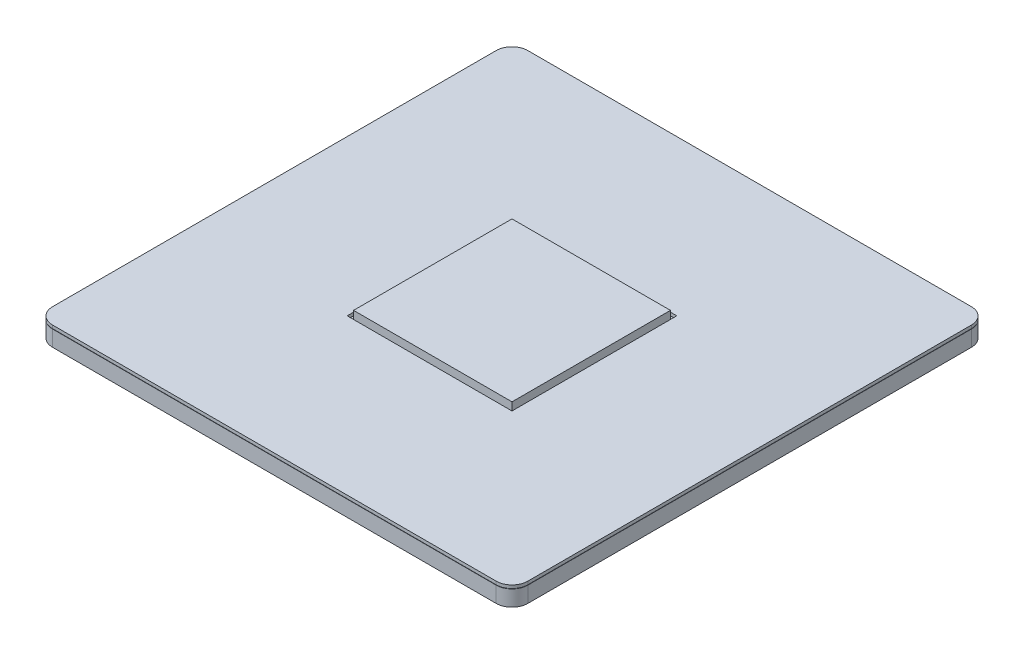
SolidWorks part; units mm, degrees
ref_plane "前视基准面" through (0, 0, 0) normal (0, 0, 1) x (1, 0, 0)
ref_plane "上视基准面" through (0, 0, 0) normal (0, 1, 0) x (1, 0, 0)
ref_plane "右视基准面" through (0, 0, 0) normal (1, 0, 0) x (0, 0, -1)
sketch "草图1" plane through (0, 0, 0) normal (0, 1, 0) x (1, 0, 0)
  line L1 (-7.5, -7.5) -> (7.5, -7.5)
  line L2 (-7.5, -7.5) -> (-7.5, 7.5)
  line L3 (-7.5, 7.5) -> (7.5, 7.5)
  line L4 (7.5, -7.5) -> (7.5, 7.5)
  line L5 (-7.5, -7.5) -> (7.5, 7.5) construction
  line L6 (-7.5, 7.5) -> (7.5, -7.5) construction
  point P0 (0, 0)
  dimension "D1" = 15
  dimension "D2" = 45
extrude "凸台-拉伸1" add sketch "草图1" along normal blind 0.5
fillet "圆角1" radius 0.5 4 edges at (-7.5, 0.25, 7.5) (-7.5, 0.25, -7.5) (7.5, 0.25, -7.5) (7.5, 0.25, 7.5)
ref_plane "基准面1" through (0, 0.51, 0) normal (0, 1, 0) x (1, 0, 0)
sketch "草图2" plane through (0, 0.51, 0) normal (0, 1, 0) x (1, 0, 0)
  line L1 (-2.6, -2.6) -> (2.6, -2.6)
  line L2 (-2.6, -2.6) -> (-2.6, 2.6)
  line L3 (-2.6, 2.6) -> (2.6, 2.6)
  line L4 (-7.5, 7) -> (-7.5, -7)
  line L5 (-7, -7.5) -> (7, -7.5)
  line L6 (7.5, -7) -> (7.5, 7)
  line L7 (7, 7.5) -> (-7, 7.5)
  line L8 (-7.5, 7) -> (-7.5, -7)
  line L9 (-7, -7.5) -> (7, -7.5)
  line L10 (7.5, -7) -> (7.5, 7)
  line L11 (7, 7.5) -> (-7, 7.5)
  line L12 (2.6, -2.6) -> (2.6, 2.6)
  line L13 (-2.6, -2.6) -> (2.6, 2.6) construction
  line L14 (-2.6, 2.6) -> (2.6, -2.6) construction
  arc A4 (-7.5, -7) -> (-7, -7.5) centre (-7, -7) ccw
  arc A5 (7, -7.5) -> (7.5, -7) centre (7, -7) ccw
  arc A6 (7.5, 7) -> (7, 7.5) centre (7, 7) ccw
  arc A7 (-7, 7.5) -> (-7.5, 7) centre (-7, 7) ccw
  arc A8 (-7.5, -7) -> (-7, -7.5) centre (-7, -7) ccw
  arc A9 (7, -7.5) -> (7.5, -7) centre (7, -7) ccw
  arc A10 (7.5, 7) -> (7, 7.5) centre (7, 7) ccw
  arc A11 (-7, 7.5) -> (-7.5, 7) centre (-7, 7) ccw
  point P2 (0, 0)
  dimension "D2" = 5.2
  dimension "D3" = 45
  dimension "D1" = 0
extrude "凸台-拉伸2" add sketch "草图2" along normal blind 0.1
sketch "草图3" plane through (0, 0.51, 0) normal (0, 1, 0) x (1, 0, 0)
  line L1 (-2.5, -2.5) -> (2.5, -2.5)
  line L2 (-2.5, -2.5) -> (-2.5, 2.5)
  line L3 (-2.5, 2.5) -> (2.5, 2.5)
  line L4 (2.5, -2.5) -> (2.5, 2.5)
  line L5 (-2.5, -2.5) -> (2.5, 2.5) construction
  line L6 (-2.5, 2.5) -> (2.5, -2.5) construction
  point P0 (0, 0)
  dimension "D1" = 5
  dimension "D2" = 45
extrude "凸台-拉伸3" add sketch "草图3" along normal blind 0.25 separate body
ref_plane "基准面2" through (0, 0, 0) normal (-1, 0, 0) x (0, 0, 1)
ref_plane "基准面3" through (0, 0, 0) normal (0, 0, -1) x (-1, 0, 0)
